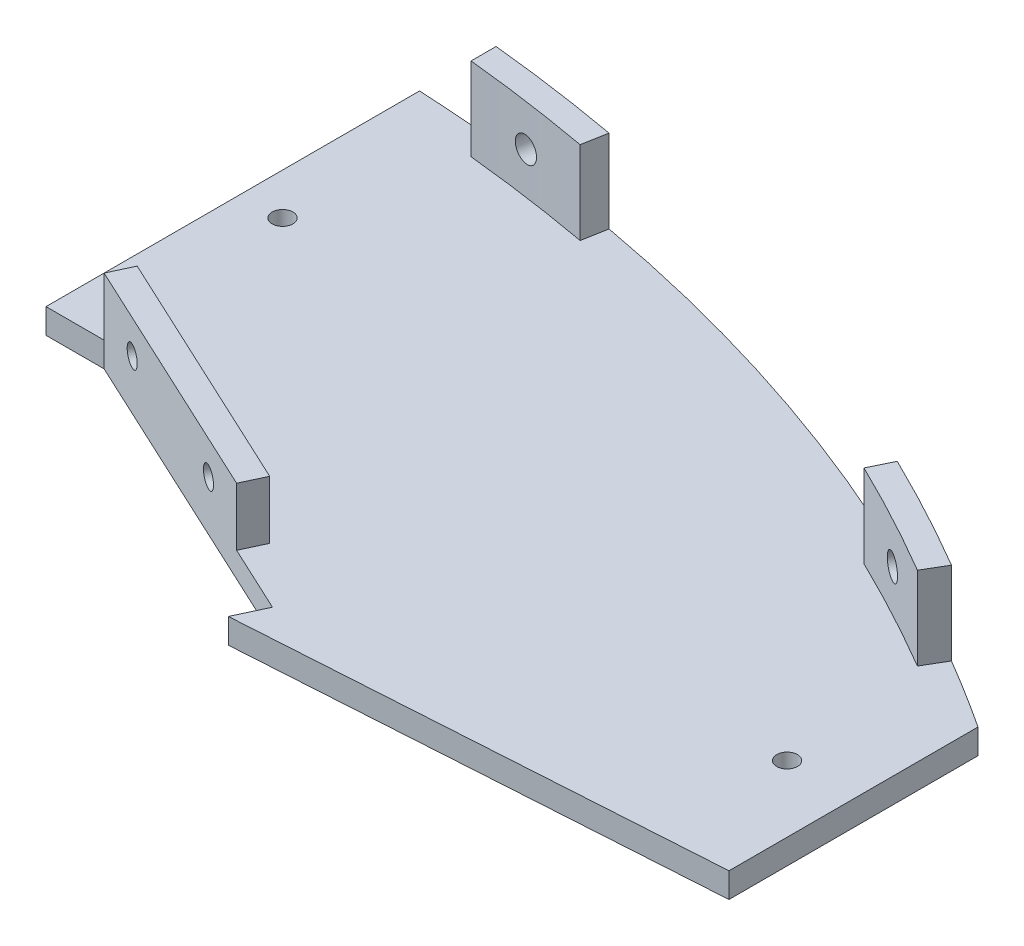
SolidWorks part; units mm, degrees
ref_plane "Front Plane" through (0, 0, 0) normal (0, 0, 1) x (1, 0, 0)
ref_plane "Top Plane" through (0, 0, 0) normal (0, 1, 0) x (1, 0, 0)
ref_plane "Right Plane" through (0, 0, 0) normal (1, 0, 0) x (0, 0, -1)
sketch "Sketch1" plane through (0, 0, 0) normal (0, 1, 0) x (1, 0, 0)
  line L0 (0, 45) -> (0, 0)
  line L1 (0, 0) -> (7, 0)
  line L2 (7, 0) -> (45.0015, -17.7204)
  line L3 (45.0015, -17.7204) -> (43.311, -21.3456)
  line L4 (43.311, -21.3456) -> (100.0015, -21.3456) construction
  line L5 (100.0015, -21.3456) -> (100.0015, -17.7204) construction
  line L6 (45.0015, -17.7204) -> (100.0015, -17.7204) construction
  line L7 (100.0015, -17.7204) -> (100.0015, 12.2796)
  line L8 (43.311, -21.3456) -> (100.0015, -17.7204)
  arc A0 (0, 45) -> (100.0015, 12.2796) centre (-10.0041, -154.7496) cw
  dimension "D5" = 4
  dimension "D7" = 30
  dimension "D8" = 200
  dimension "D1" = 45
  dimension "D2" = 7
  dimension "D3" = 41.93
  dimension "D4" = 155
  dimension "D6" = 55
extrude "Boss-Extrude1" add sketch "Sketch1" along normal blind 3
sketch "Sketch2" plane through (1.2502, 0, -2.6812) normal (-0.4226, 0, 0.9063) x (0.9063, 0, 0.4226)
  line L0 (6.3442, 0) -> (6.3442, 10)
  line L1 (6.3442, 10) -> (39.3442, 10)
  line L2 (39.3442, 10) -> (39.3442, 0)
  line L3 (39.3442, 0) -> (6.3442, 0)
  line L4 (13.3442, 6) -> (13.3442, 3) construction
  line L5 (6.3442, 3) -> (48.2742, 3) construction
  circle A0 centre (13.3442, 6) radius 1.25
  circle A1 centre (32.3442, 6) radius 1.25
  dimension "D1" = 2.5
  dimension "D5" = 19
  dimension "D6" = 7
  dimension "D2" = 3
  dimension "D3" = 4
  dimension "D4" = 7
extrude "Boss-Extrude2" add sketch "Sketch2" against normal blind 3
sketch "Sketch3" plane through (0, 0, 0) normal (0, -1, 0) x (1, 0, 0)
  line L0 (0, -45) -> (0, -23.5) construction
  line L1 (0, -45) -> (0, 0) construction
  line L2 (0, -23.5) -> (5, -23.5) construction
  line L3 (92.0015, 2.7204) -> (100.0015, 2.7204) construction
  line L4 (100.0015, 17.7204) -> (100.0015, -12.2796) construction
  circle A0 centre (5, -23.5) radius 1.25
  circle A1 centre (92.0015, 2.7204) radius 1.25
  dimension "D1" = 21.5
  dimension "D3" = 2.5
  dimension "D4" = 8
  dimension "D2" = 5
extrude "Cut-Extrude1" cut sketch "Sketch3" against normal through all
sketch "Sketch6" plane through (0, 3, 0) normal (0, 1, 0) x (1, 0, 0)
  line L0 (0, 45) -> (0, 0) construction
  line L1 (100.0015, -17.7204) -> (100.0015, 12.2796) construction
  line L2 (9.9719, 44.2503) -> (9.9719, 41.2388)
  line L3 (25.8152, 42.0167) -> (25.2786, 39.0689)
  line L4 (91.5151, 17.5694) -> (89.9943, 14.9879)
  line L5 (77.4158, 25.133) -> (76.1061, 22.4382)
  arc A0 (0, 45) -> (100.0015, 12.2796) centre (-10.0041, -154.7496) cw
  arc A1 (100.0015, 12.2796) -> (0, 45) centre (-10.0041, -154.7496) ccw construction
  arc A2 (0, 42) -> (100.0015, 8.6801) centre (-10.0041, -154.7496) cw
  arc M11 (100.0015, 12.2796) -> (0, 45) centre (-10.0041, -154.7496) ccw
  dimension "D1" = 3
  dimension "D2" = 10
  dimension "D3" = 16
  dimension "D4" = 10
  dimension "D5" = 16
extrude "Boss-Extrude3" add sketch "Sketch6" along normal blind 10 contours L2 A2 L3 M11 | L5 A2 L4 M11
sketch "Sketch7" plane through (0, 13, 0) normal (0, 1, 0) x (1, 0, 0)
  line L0 (17.9159, 43.292) -> (-10.0041, -154.7496) construction
  line L1 (-10.0041, -154.7496) -> (84.5411, 21.4922) construction
  arc A0 (25.8152, 42.0167) -> (9.9719, 44.2503) centre (-10.0041, -154.7496) ccw construction
  arc A1 (91.5151, 17.5694) -> (77.4158, 25.133) centre (-10.0041, -154.7496) ccw construction
ref_plane "Plane1" through (17.9159, 13, -43.292) normal (0.1396, 0, -0.9902) x (-0.9902, 0, -0.1396)
sketch "Sketch8" plane through (17.9159, 13, -43.292) normal (0.1396, 0, -0.9902) x (-0.9902, 0, -0.1396)
  line L0 (-8, 0) -> (8, -10) construction
  circle A0 centre (0, -5) radius 1.5
  dimension "D1" = 3
extrude "Cut-Extrude2" cut sketch "Sketch8" against normal up to surface (3.0019 mm away)
ref_plane "Plane2" through (84.5411, 13, -21.4922) normal (0.4727, 0, -0.8812) x (-0.8812, 0, -0.4727)
sketch "Sketch9" plane through (84.5411, 13, -21.4922) normal (0.4727, 0, -0.8812) x (-0.8812, 0, -0.4727)
  line L0 (-8, 0) -> (8, -10) construction
  circle A0 centre (0, -5) radius 1.5
  dimension "D1" = 3
extrude "Cut-Extrude3" cut sketch "Sketch9" against normal up to surface (3.0019 mm away)
